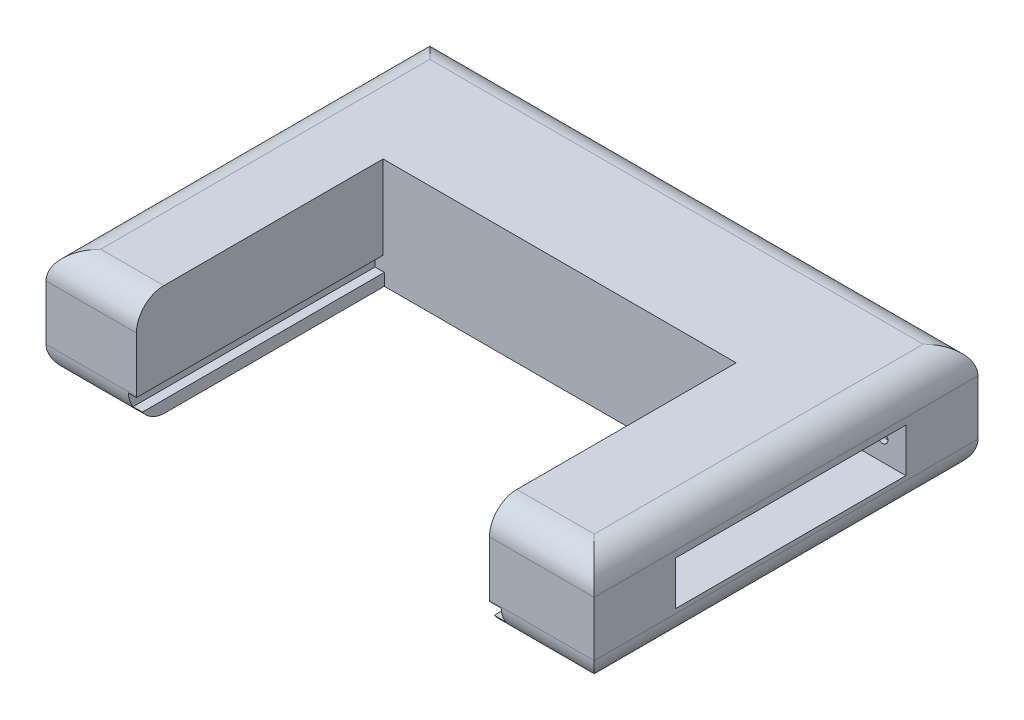
SolidWorks part; units mm, degrees
ref_plane "Front Plane" through (0, 0, 0) normal (0, 0, 1) x (1, 0, 0)
ref_plane "Top Plane" through (0, 0, 0) normal (0, 1, 0) x (1, 0, 0)
ref_plane "Right Plane" through (0, 0, 0) normal (1, 0, 0) x (0, 0, -1)
sketch "Sketch1" plane through (0, 0, 0) normal (0, 1, 0) x (1, 0, 0)
  line L1 (-26.38, 14.1762) -> (23.62, 14.1762)
  line L2 (-26.38, 14.1762) -> (-26.38, -20.8238)
  line L3 (-26.38, -20.8238) -> (23.62, -20.8238)
  line L4 (23.62, 14.1762) -> (23.62, -20.8238)
  dimension "D1" = 50
  dimension "D2" = 35
extrude "Boss-Extrude1" add sketch "Sketch1" along normal blind 10
sketch "Sketch2" plane through (0, 0, 20.8238) normal (0, 0, 1) x (1, 0, 0)
  line L1 (-18.8678, 2.4017) -> (15.1322, 2.4017)
  line L2 (-18.8678, 2.4017) -> (-18.8678, 1.1017)
  line L3 (-18.8678, 1.1017) -> (15.1322, 1.1017)
  line L4 (15.1322, 2.4017) -> (15.1322, 1.1017)
  dimension "D1" = 34
  dimension "D2" = 1.3
extrude "Cut-Extrude1" cut sketch "Sketch2" against normal blind 22.5 contours L2 L1 L4 L3
sketch "Sketch3" plane through (0, 0, 20.8238) normal (0, 0, 1) x (1, 0, 0)
  line L0 (-18.8678, 2.4017) -> (15.1322, 2.4017) construction
  line L1 (-0.9352, 2.4017) -> (14.0648, 2.4017)
  line L2 (-0.9352, 2.4017) -> (-0.9352, 10)
  line L3 (-0.9352, 10) -> (14.0648, 10)
  line L4 (14.0648, 2.4017) -> (14.0648, 10)
  line L5 (-26.38, 10) -> (23.62, 10) construction
  line L7 (-0.9352, 2.4017) -> (-18.8678, 2.4017)
  line L8 (-0.9352, 2.4017) -> (-0.9352, 10)
  line L9 (-0.9352, 10) -> (-18.8678, 10)
  line L10 (-18.8678, 2.4017) -> (-18.8678, 10)
  line M12 (-18.8678, 2.4017) -> (15.1322, 2.4017)
  line M15 (23.62, 10) -> (-26.38, 10)
  dimension "D1" = 15
  dimension "D2" = 17.9326
extrude "Cut-Extrude2" cut sketch "Sketch3" against normal blind 22.5 contours L4 L2 M12 M15
sketch "Sketch4" plane through (0, 0, 20.8238) normal (0, 0, 1) x (1, 0, 0)
  line L0 (-26.38, 10) -> (-0.9352, 10) construction
  line L1 (-0.9352, 2.4017) -> (-18.1352, 2.4017)
  line L2 (-0.9352, 2.4017) -> (-0.9352, 10)
  line L3 (-0.9352, 10) -> (-18.1352, 10)
  line L4 (-18.1352, 2.4017) -> (-18.1352, 10)
  dimension "D1" = 17.2
extrude "Cut-Extrude3" cut sketch "Sketch4" against normal blind 22.5 contours L2 L1 L4 L3
sketch "Sketch5" plane through (0, 0, 20.8238) normal (0, 0, 1) x (1, 0, 0)
  line L5 (-18.8678, 1.1017) -> (15.1322, 1.1017) construction
  line L6 (0.5796, 1.1017) -> (14.0796, 1.1017)
  line L7 (0.5796, 1.1017) -> (0.5796, 0)
  line L8 (0.5796, 0) -> (14.0796, 0)
  line L9 (14.0796, 1.1017) -> (14.0796, 0)
  line L10 (-26.38, 0) -> (23.62, 0) construction
  dimension "D1" = 13.5
extrude "Cut-Extrude4" cut sketch "Sketch5" against normal blind 22.5
sketch "Sketch6" plane through (0, 0, 20.8238) normal (0, 0, 1) x (1, 0, 0)
  line L0 (-26.38, 0) -> (0.5796, 0) construction
  line L1 (0.5796, 1.1017) -> (-18.0204, 1.1017)
  line L2 (0.5796, 1.1017) -> (0.5796, 0)
  line L3 (0.5796, 0) -> (-18.0204, 0)
  line L4 (-18.0204, 1.1017) -> (-18.0204, 0)
  dimension "D1" = 18.6
extrude "Cut-Extrude5" cut sketch "Sketch6" against normal blind 22.5
sketch "Sketch7" plane through (-26.38, 0, 0) normal (-1, 0, 0) x (0, 0, 1)
  line L1 (-7.1516, 6.7188) -> (13.8484, 6.7188)
  line L2 (-7.1516, 6.7188) -> (-7.1516, 2.7188)
  line L3 (-7.1516, 2.7188) -> (13.8484, 2.7188)
  line L4 (13.8484, 6.7188) -> (13.8484, 2.7188)
  dimension "D1" = 21
  dimension "D2" = 4
extrude "Cut-Extrude6" cut sketch "Sketch7" against normal blind 4 contours L2 L1 L4 L3
sketch "Sketch8" plane through (0, 0, -7.1516) normal (0, 0, 1) x (1, 0, 0)
  circle A0 centre (-24.1657, 4.7772) radius 0.5
  dimension "D1" = 1
extrude "Cut-Extrude7" cut sketch "Sketch8" against normal blind 0.5 contours A0
sketch "Sketch9" plane through (0, 0, 13.8484) normal (0, 0, -1) x (-1, 0, 0)
  circle A0 centre (24.2474, 4.8198) radius 0.5
  dimension "D1" = 1
extrude "Cut-Extrude8" cut sketch "Sketch9" against normal blind 0.5 contours A0
sketch "Sketch10" plane through (23.62, 0, 0) normal (1, 0, 0) x (0, 0, -1)
  line L1 (-13.4045, 6.9045) -> (7.5955, 6.9045)
  line L2 (-13.4045, 6.9045) -> (-13.4045, 2.9045)
  line L3 (-13.4045, 2.9045) -> (7.5955, 2.9045)
  line L4 (7.5955, 6.9045) -> (7.5955, 2.9045)
  dimension "D1" = 21
  dimension "D2" = 4
extrude "Cut-Extrude9" cut sketch "Sketch10" against normal blind 4
sketch "Sketch11" plane through (0, 0, 13.4045) normal (0, 0, -1) x (-1, 0, 0)
  circle A0 centre (-21.4901, 4.9862) radius 0.5
  point P2 (0, 0)
  dimension "D1" = 1
extrude "Cut-Extrude10" cut sketch "Sketch11" against normal blind 0.5 contours A0
sketch "Sketch12" plane through (0, 0, -7.5955) normal (0, 0, 1) x (1, 0, 0)
  circle A0 centre (21.4823, 4.8927) radius 0.5
  point P2 (0, 0)
  point P3 (0, 0)
  point P4 (0, 0)
  dimension "D1" = 1
extrude "Cut-Extrude11" cut sketch "Sketch12" against normal blind 0.5 contours A0
fillet "Fillet1" radius 2.5 10 edges at (-22.2002, 0, 20.8238) (18.8498, 0, 20.8238) (-26.38, 0, 3.3238) (-26.38, 10, 3.3238) (-22.2576, 10, 20.8238) (18.8424, 10, 20.8238) (-1.38, 0, -14.1762) (-1.38, 10, -14.1762) (23.62, 0, 3.3238) (23.62, 10, 3.3238)
